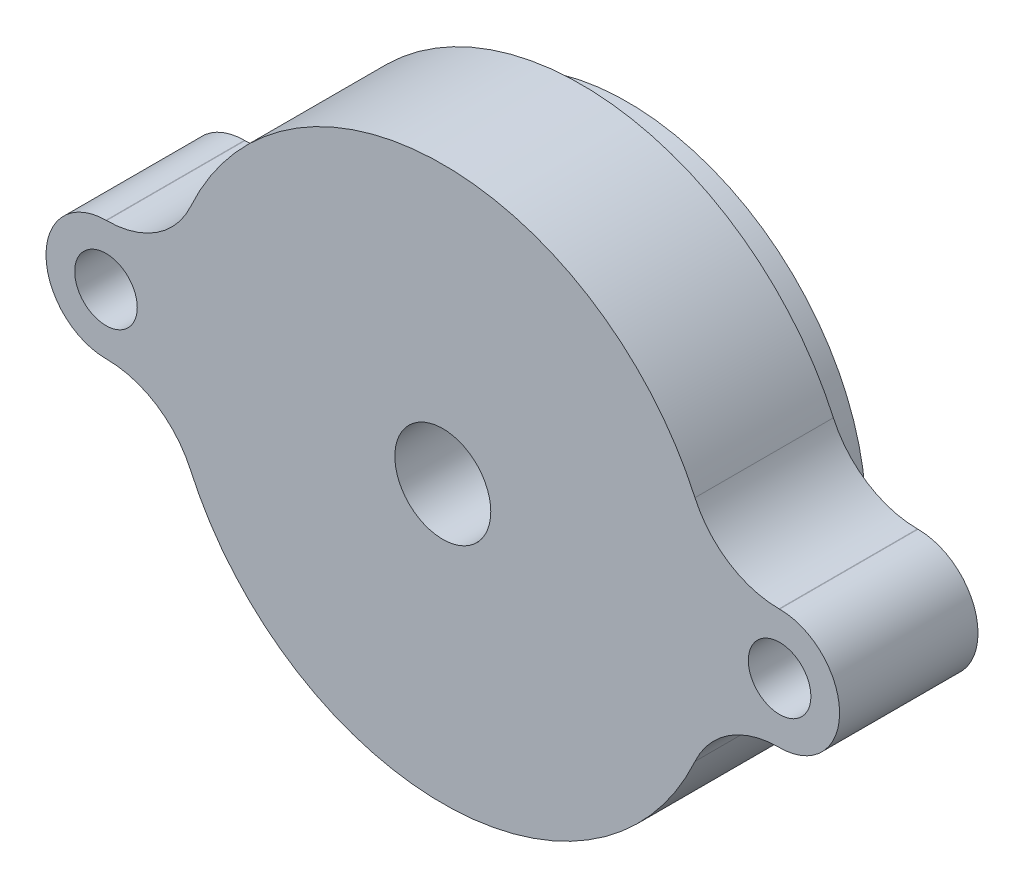
SolidWorks part; units mm, degrees
material "PET"
ref_plane "Front" through (0, 0, 0) normal (0, 0, 1) x (1, 0, 0)
ref_plane "Top" through (0, 0, 0) normal (0, 1, 0) x (1, 0, 0)
ref_plane "Right" through (0, 0, 0) normal (1, 0, 0) x (0, 0, -1)
sketch "Sketch1" plane through (0, 0, 0) normal (0, 0, 1) x (1, 0, 0)
  line L0 (23.1775, 2.8575) -> (16.1706, 2.8575)
  line L1 (23.1775, -2.8575) -> (16.1706, -2.8575)
  line L2 (0, 16.4211) -> (0, -16.4211) construction
  line L3 (-23.1775, -2.8575) -> (-16.1706, -2.8575)
  line L4 (-23.1775, 2.8575) -> (-16.1706, 2.8575)
  circle A0 centre (0, 0) radius 16.4211 construction
  arc A1 (16.1706, 2.8575) -> (-16.1706, 2.8575) centre (0, 0) ccw
  circle A2 centre (0, 0) radius 3.302 construction
  circle A3 centre (0, 0) radius 3.302
  arc A4 (-16.1706, -2.8575) -> (16.1706, -2.8575) centre (0, 0) ccw
  arc A5 (23.1775, -2.8575) -> (23.1775, 2.8575) centre (23.1775, 0) ccw
  arc A6 (23.1775, -2.8575) -> (23.1775, 2.8575) centre (23.1775, 0) ccw
  arc A7 (-23.1775, -2.8575) -> (-23.1775, 2.8575) centre (-23.1775, 0) cw
  arc A8 (-16.1706, 2.8575) -> (-16.1706, -2.8575) centre (0, 0) ccw
  arc A9 (16.1706, 2.8575) -> (16.1706, -2.8575) centre (0, 0) cw
  dimension "D1" = 1.27
extrude "Boss-Extrude1" add sketch "Sketch1" along normal blind 6.35 contours L2 A1 A8 A4 A3 | A1 L2 A3 A4 A9
sketch "Sketch2" plane through (0, 0, 6.35) normal (0, 0, 1) x (1, 0, 0)
  line L4 (23.1775, 4.1275) -> (23.1383, 4.1275)
  line L5 (-23.1383, 4.1275) -> (-23.1775, 4.1275)
  line L6 (-23.1775, -4.1275) -> (-23.1383, -4.1275)
  line L7 (23.1383, -4.1275) -> (23.1775, -4.1275)
  line L8 (23.1775, 4.1275) -> (23.1383, 4.1275)
  line L9 (-23.1383, 4.1275) -> (-23.1775, 4.1275)
  line L10 (-23.1775, -4.1275) -> (-23.1383, -4.1275)
  line L11 (23.1383, -4.1275) -> (23.1775, -4.1275)
  circle A1 centre (0, 0) radius 16.4211
  circle A2 centre (0, 0) radius 16.4211
  arc A8 (17.3537, 7.8581) -> (23.1383, 4.1275) centre (23.1383, 10.4775) ccw
  arc A9 (17.3537, 7.8581) -> (-17.3537, 7.8581) centre (0, 0) ccw
  arc A10 (-23.1383, 4.1275) -> (-17.3537, 7.8581) centre (-23.1383, 10.4775) ccw
  arc A11 (-23.1775, 4.1275) -> (-23.1775, -4.1275) centre (-23.1775, 0) ccw
  arc A12 (-17.3537, -7.8581) -> (-23.1383, -4.1275) centre (-23.1383, -10.4775) ccw
  arc A13 (-17.3537, -7.8581) -> (17.3537, -7.8581) centre (0, 0) ccw
  arc A14 (23.1383, -4.1275) -> (17.3537, -7.8581) centre (23.1383, -10.4775) ccw
  arc A15 (23.1775, -4.1275) -> (23.1775, 4.1275) centre (23.1775, 0) ccw
  arc A16 (17.3537, 7.8581) -> (23.1383, 4.1275) centre (23.1383, 10.4775) ccw
  arc A17 (17.3537, 7.8581) -> (-17.3537, 7.8581) centre (0, 0) ccw
  arc A18 (-23.1383, 4.1275) -> (-17.3537, 7.8581) centre (-23.1383, 10.4775) ccw
  arc A19 (-23.1775, 4.1275) -> (-23.1775, -4.1275) centre (-23.1775, 0) ccw
  arc A20 (-17.3537, -7.8581) -> (-23.1383, -4.1275) centre (-23.1383, -10.4775) ccw
  arc A21 (-17.3537, -7.8581) -> (17.3537, -7.8581) centre (0, 0) ccw
  arc A22 (23.1383, -4.1275) -> (17.3537, -7.8581) centre (23.1383, -10.4775) ccw
  arc A23 (23.1775, -4.1275) -> (23.1775, 4.1275) centre (23.1775, 0) ccw
  dimension "D1" = 0
  dimension "D2" = 0
extrude "Boss-Extrude3" add sketch "Sketch2" against normal blind 3.175 and the other way blind 6.35
hole_wizard "#6 Clearance Hole1" positions "Sketch21" profile "Sketch3" hole size "#6" standard "ANSI Inch" end condition up to next
sketch "Sketch21" plane through (-22.6996, 0.1044, 3.175) normal (0, 0, -1) x (-1, 0, 0)
  point P0 (-45.8771, -0.1044)
  point P3 (0.4779, -0.1044)
sketch "Sketch3" plane through (23.1775, 0, 3.175) normal (1, 0, 0) x (0, 1, 0)
  line L0 (0, 0) -> (0, 9.525)
  line L1 (0, 9.525) -> (2.1526, 9.525)
  line L2 (2.1526, 9.525) -> (2.1526, 0)
  line L5 (2.1526, 0) -> (0, 0)
  line L11 (0, -6.35) -> (0, 107.95) construction
  dimension "Thru Hole Dia." = 4.3053
  dimension "Thru Hole Depth" = 9.525
hole_wizard "#6 Plastic Insert" positions "Sketch4" profile "Sketch5" legacy
sketch "Sketch4" plane through (-45.3006, 0, 3.175) normal (0, 0, -1) x (-1, 0, 0)
  point P0 (-68.4781, 0)
  point P3 (-22.1231, 0)
sketch "Sketch5" plane through (23.1775, 0, 3.175) normal (1, 0, 0) x (0, 1, 0)
  line L0 (0, 0) -> (0, 3.81)
  line L1 (0, 3.81) -> (2.5273, 3.81)
  line L2 (2.5273, 3.81) -> (2.6543, 0)
  line L3 (2.6543, 0) -> (0, 0)
  line L4 (0, 110) -> (0, -10) construction
  dimension "Minor Diameter" = 5.0546
  dimension "Depth" = 3.81
  dimension "Major Diameter" = 5.3086
other "#6 Plastic Insert Hole<1>"
sketch "Sketch22" plane through (0, 0, 12.7) normal (0, 0, 1) x (1, 0, 0)
  circle A0 centre (0, 0) radius 3.302 construction
  circle A1 centre (0, 0) radius 16.4211 construction
  circle A2 centre (0, 0) radius 3.302
  circle A3 centre (0, 0) radius 16.4211
extrude "Boss-Extrude4" add sketch "Sketch22" against normal up to next
